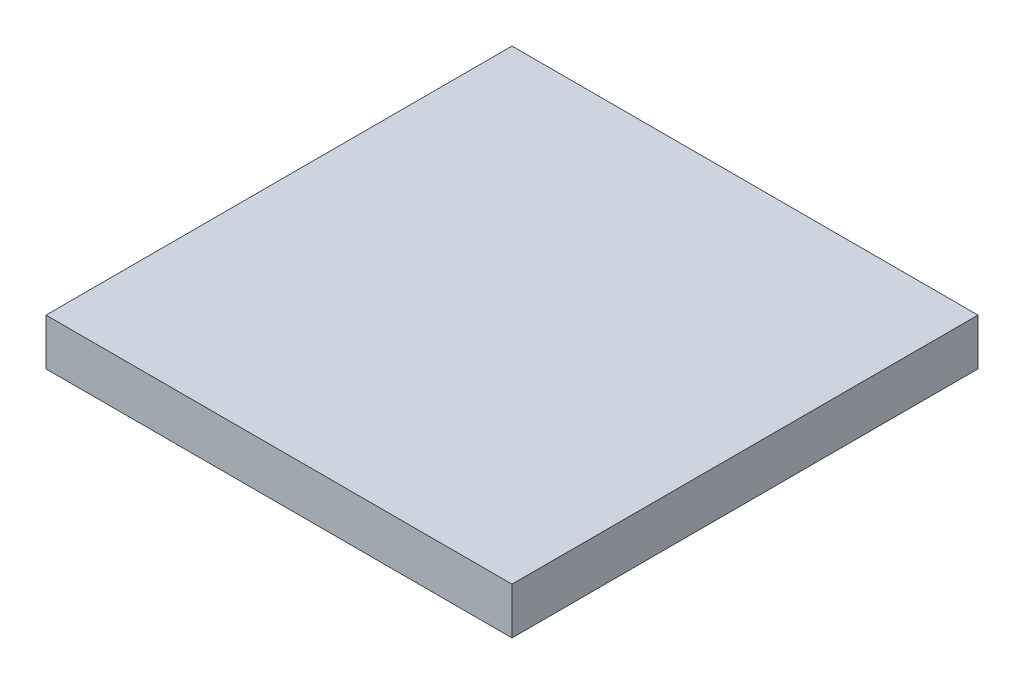
SolidWorks part; units mm, degrees
material "Alumina"
ref_plane "Front Plane" through (0, 0, 0) normal (0, 0, 1) x (1, 0, 0)
ref_plane "Top Plane" through (0, 0, 0) normal (0, 1, 0) x (1, 0, 0)
ref_plane "Right Plane" through (0, 0, 0) normal (1, 0, 0) x (0, 0, -1)
sketch "Sketch1" plane through (0, 0, 0) normal (0, 1, 0) x (1, 0, 0)
  line L0 (0, 0) -> (100, 100) construction
  line L1 (0, 0) -> (100, 0)
  line L2 (0, 0) -> (0, 100)
  line L3 (0, 100) -> (100, 100)
  line L4 (100, 0) -> (100, 100)
  line L5 (0, 100) -> (100, 0) construction
  line L6 (0, 50) -> (50, 0) construction
  line L7 (50, 100) -> (100, 50) construction
  circle A0 centre (25, 25) radius 2.5 construction
  circle A1 centre (75, 75) radius 2.5 construction
  point P5 (50, 50)
  dimension "D1" = 100
  dimension "D2" = 100
extrude "Boss-Extrude2" add sketch "Sketch1" along normal blind 10
